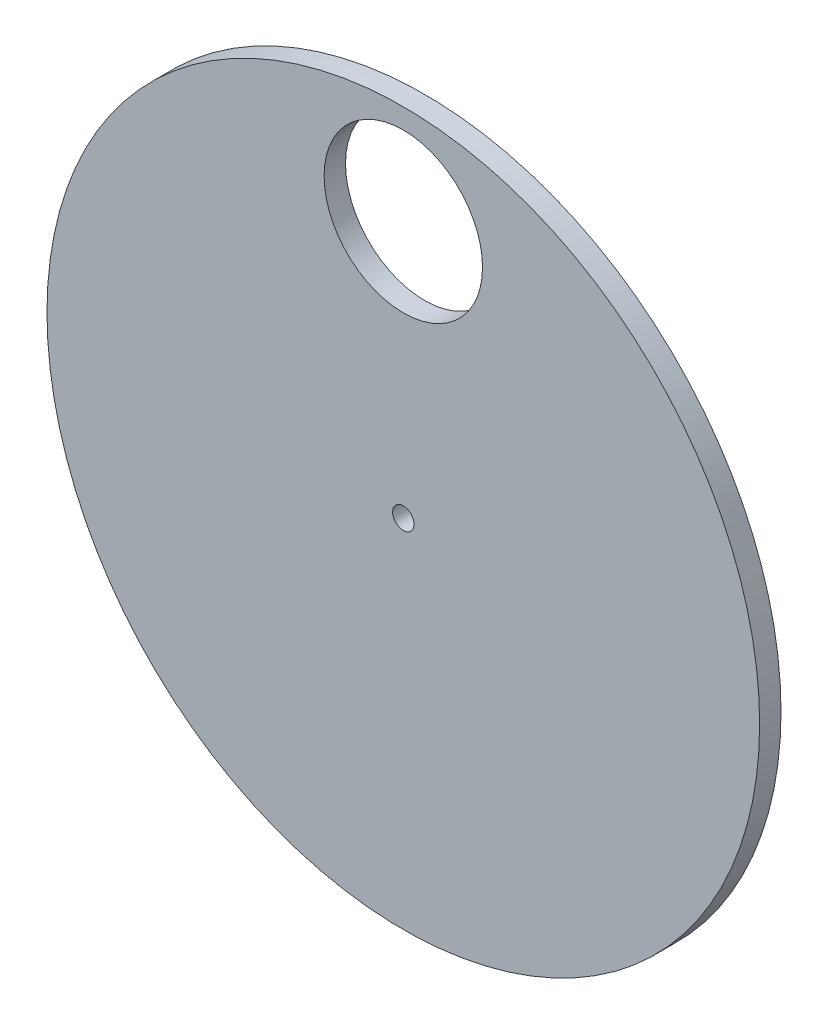
SolidWorks part; units mm, degrees
ref_plane "Front Plane" through (0, 0, 0) normal (0, 0, 1) x (1, 0, 0)
ref_plane "Top Plane" through (0, 0, 0) normal (0, 1, 0) x (1, 0, 0)
ref_plane "Right Plane" through (0, 0, 0) normal (1, 0, 0) x (0, 0, -1)
sketch "Sketch1" plane through (0, 0, 0) normal (0, 0, 1) x (1, 0, 0)
  circle A0 centre (0, 0) radius 100
extrude "Boss-Extrude1" add sketch "Sketch1" along normal blind 6
sketch "Sketch2" plane through (0, 0, 6) normal (0, 0, 1) x (1, 0, 0)
  circle A0 centre (0, 0) radius 3
extrude "Cut-Extrude1" cut sketch "Sketch2" against normal blind 6
sketch "Sketch3" plane through (0, 0, 0) normal (0, 0, -1) x (-1, 0, 0)
  circle A0 centre (0, 72.1105) radius 22.225
  dimension "D1" = 44.45
extrude "Cut-Extrude2" cut sketch "Sketch3" against normal blind 10
